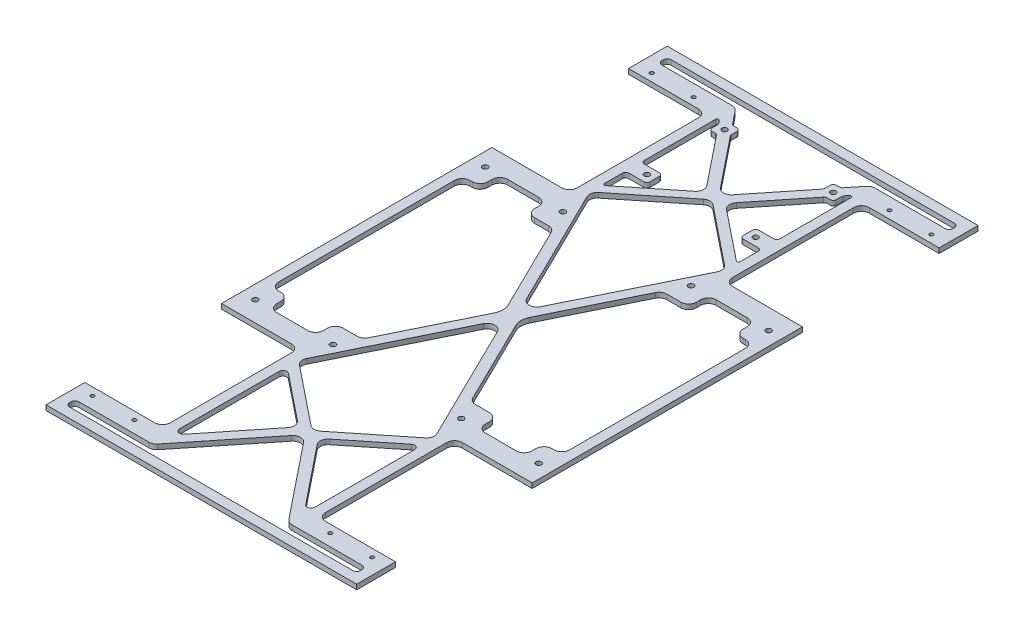
SolidWorks part; units mm, degrees
material "1060 Alloy"
ref_plane "Front Plane" through (0, 0, 0) normal (0, 0, 1) x (1, 0, 0)
ref_plane "Top Plane" through (0, 0, 0) normal (0, 1, 0) x (1, 0, 0)
ref_plane "Right Plane" through (0, 0, 0) normal (1, 0, 0) x (0, 0, -1)
sketch "Sketch1" plane through (0, 0, 0) normal (0, 1, 0) x (1, 0, 0)
  line L0 (-100, 87) -> (-100, -87)
  line L1 (-100, 200) -> (100, 200)
  line L2 (-100, 200) -> (-100, 175)
  line L3 (-100, -200) -> (100, -200)
  line L4 (100, 200) -> (100, 175)
  line L5 (-100, 175) -> (-50, 175)
  line L7 (-100, 87) -> (-50, 87)
  line L8 (-50, 175) -> (-50, 87)
  line L9 (-100, -87) -> (-50, -87)
  line L11 (-100, -175) -> (-50, -175)
  line L12 (-50, -87) -> (-50, -175)
  line L13 (100, -175) -> (50, -175)
  line L15 (100, -87) -> (50, -87)
  line L17 (100, 175) -> (50, 175)
  line L19 (100, 87) -> (50, 87)
  line L20 (50, 175) -> (50, 87)
  line L21 (-100, -175) -> (-100, -200)
  line L22 (100, 87) -> (100, -87)
  line L23 (100, -175) -> (100, -200)
  line L24 (50, -87) -> (50, -175)
  point P4 (0, 200)
  point P6 (100, 0)
  dimension "D1" = 400
  dimension "D2" = 200
  dimension "D3" = 88
  dimension "D4" = 25
  dimension "D5" = 50
extrude "Boss-Extrude1" add sketch "Sketch1" along normal blind 3.175
hole_wizard "3/32 (0.09375) Diameter Hole1" positions "Sketch3" profile "Sketch4" hole size "3/32" standard "ANSI Inch" end condition up to next
sketch "Sketch3" plane through (0, 3.175, 0) normal (0, 1, 0) x (1, 0, 0)
  line L0 (-90, 180) -> (-63.06, 180) construction
  line L5 (-100, 175) -> (-50, 175) construction
  line L6 (-100, 200) -> (-100, 175) construction
  point P0 (-90, 180)
  point P2 (-63.06, 180)
  dimension "D1" = 26.94
  dimension "D2" = 5
  dimension "D3" = 10
  dimension "D4" = 26.94
sketch "Sketch4" plane through (-90, 3.175, -180) normal (1, 0, 0) x (0, 0, 1)
  line L0 (0, 0) -> (0, 3.175)
  line L1 (0, 3.175) -> (1.1906, 3.175)
  line L2 (1.1906, 3.175) -> (1.1906, 0)
  line L5 (1.1906, 0) -> (0, 0)
  line L11 (0, -6.35) -> (0, 107.95) construction
  dimension "Thru Hole Dia." = 2.3812
  dimension "Thru Hole Depth" = 3.175
mirror "Mirror5" about plane through (0, 0, 0) normal (1, 0, 0) of "3/32 (0.09375) Diameter Hole1" second plane through (0, 0, 0) second plane normal (0, 0, 1)
sketch "Sketch5" plane through (0, 3.175, 0) normal (0, 1, 0) x (1, 0, 0)
  line L3 (-34.9422, 61.6) -> (-52.125, 61.6)
  line L4 (-93.65, 61.6) -> (-93.65, 0)
  line L5 (-93.65, 0) -> (-4.7456, 0)
  line L6 (-4.7456, 0) -> (-34.9422, 61.6)
  line L9 (-43.65, 177.5456) -> (-43.65, 101.1091)
  line L10 (-43.65, 101.1091) -> (-6.35, 131)
  line L11 (-6.35, 131) -> (-43.65, 177.5456)
  line L12 (-43.65, 93.79) -> (0, 128.7696)
  line L13 (0, 128.7696) -> (0, 4.7456)
  line L14 (0, 4.7456) -> (-43.65, 93.79)
  line L15 (-93.65, 193.65) -> (-93.65, 187.7)
  line L16 (-93.65, 187.7) -> (-43.65, 187.7)
  line L17 (-43.65, 187.7) -> (0, 133.2304)
  line L18 (0, 133.2304) -> (0, 193.65)
  line L19 (0, 193.65) -> (-93.65, 193.65)
  line L20 (-50, 175) -> (-50, 87) construction
  line L21 (0, 128.7696) -> (0, 133.2304) construction
  line L22 (100, 200) -> (-100, 200) construction
  line L23 (-100, 87) -> (-100, -87) construction
  line L24 (-100, 200) -> (-100, 175) construction
  line L25 (-100, 175) -> (-50, 175) construction
  line L26 (-50, 87) -> (-100, 87) construction
  line L27 (-4.7456, 0) -> (0, 0) construction
  line L28 (0, 0) -> (0, 4.7456) construction
  line L29 (-82.125, 61.6) -> (-93.65, 61.6)
  line L31 (-82.125, 61.6) -> (-82.125, 74.3)
  line L32 (-82.125, 74.3) -> (-52.125, 74.3)
  line L33 (-52.125, 61.6) -> (-52.125, 74.3)
  point P9 (0, 131)
  point P19 (-50, 131)
  dimension "D1" = 6.35
  dimension "D2" = 6.35
  dimension "D3" = 6.35
  dimension "D4" = 6.35
  dimension "D5" = 12.7
  dimension "D6" = 25.4
  dimension "D7" = 6.35
  dimension "D8" = 6.35
  dimension "D9" = 6.35
  dimension "D10" = 12.7
  dimension "D11" = 30
  dimension "D12" = 2.125
extrude "Cut-Extrude1" cut sketch "Sketch5" against normal through all both and the other way through all
mirror "Mirror6" about plane through (0, 0, 0) normal (1, 0, 0) of "Cut-Extrude1" second plane through (0, 0, 0) second plane normal (0, 0, 1)
hole_wizard "Ø3.5 (3.5) Diameter Hole1" positions "Sketch6" profile "Sketch7" hole size "Ø3.5" standard "ANSI Metric" end condition up to next
sketch "Sketch6" plane through (0, 0, 0) normal (0, -1, 0) x (-1, 0, 0)
  line L0 (41.24, 74) -> (91.24, 74) construction
  line L2 (50, 87) -> (100, 87) construction
  line L3 (91.24, 74) -> (100, 74) construction
  line L4 (100, 87) -> (100, -87) construction
  point P0 (41.24, 74)
  point P2 (91.24, 74)
  dimension "D1" = 50
  dimension "D2" = 8.76
  dimension "D3" = 13
sketch "Sketch7" plane through (-41.24, 0, -74) normal (1, 0, 0) x (0, 0, -1)
  line L0 (0, 0) -> (0, 3.175)
  line L1 (0, 3.175) -> (1.75, 3.175)
  line L2 (1.75, 3.175) -> (1.75, 0)
  line L5 (1.75, 0) -> (0, 0)
  line L11 (0, -6.35) -> (0, 107.95) construction
  dimension "Thru Hole Dia." = 3.5
  dimension "Thru Hole Depth" = 3.175
mirror "Mirror7" about plane through (0, 0, 0) normal (1, 0, 0) of "Ø3.5 (3.5) Diameter Hole1" second plane through (0, 0, 0) second plane normal (0, 0, 1)
sketch "Sketch8" plane through (0, 3.175, 0) normal (0, 1, 0) x (1, 0, 0)
  line L0 (-35, 171.8287) -> (35, 171.8287) construction
  line L1 (-40, 116.8287) -> (-30, 116.8287)
  line L3 (-40, 126.8287) -> (-30, 126.8287)
  line L4 (-30, 116.8287) -> (-30, 126.8287)
  line L13 (30, 116.8287) -> (40, 116.8287)
  line L14 (30, 116.8287) -> (30, 126.8287)
  line L15 (30, 126.8287) -> (40, 126.8287)
  line L17 (35, 171.8287) -> (35, 121.8287) construction
  line L18 (35, 121.8287) -> (-35, 121.8287) construction
  line L19 (-35, 121.8287) -> (-35, 171.8287) construction
  line L20 (-40, 166.8287) -> (-40, 176.8287)
  line L21 (-37.4776, 169.8432) -> (-32.5224, 173.8142) construction
  line L23 (-6.35, 131) -> (-43.65, 177.5456) construction
  line L24 (-43.65, 187.7) -> (0, 133.2304) construction
  line L29 (-43.65, 177.5456) -> (-43.65, 101.1091) construction
  line L36 (-40, 166.8287) -> (-30, 166.8287)
  line L38 (-40, 126.8287) -> (-43.65, 126.8287)
  line L41 (30, 166.8287) -> (40, 166.8287)
  line L44 (-40, 176.8287) -> (-30, 176.8287)
  line L45 (-30, 176.8287) -> (-30, 166.8287)
  line L46 (30, 166.8287) -> (30, 176.8287)
  line L47 (30, 176.8287) -> (40, 176.8287)
  line L48 (40, 176.8287) -> (40, 166.8287)
  line L49 (-40, 116.8287) -> (-43.65, 116.8287)
  line L50 (-43.65, 126.8287) -> (-43.65, 116.8287)
  line L51 (43.65, 177.5456) -> (43.65, 101.1091) construction
  line L52 (40, 126.8287) -> (43.65, 126.8287)
  line L54 (40, 116.8287) -> (43.65, 116.8287)
  line L55 (43.65, 126.8287) -> (43.65, 116.8287)
  point P22 (-35, 166.8287)
  point P23 (35, 166.8287)
  point P24 (-35, 126.8287)
  point P25 (30, 121.8287)
  point P26 (35, 126.8287)
  point P27 (-30, 121.8287)
  point P29 (0, 171.8287)
  point P34 (-35, 171.8287)
  dimension "D1" = 10
  dimension "D2" = 10
  dimension "D3" = 70
  dimension "D4" = 50
  dimension "D5" = 10
  dimension "D6" = 10
  dimension "D7" = 5
  dimension "D8" = 10
  dimension "D9" = 13.65
  dimension "D10" = 13.65
extrude "Boss-Extrude2" add sketch "Sketch8" against normal up to surface (3.175 mm away) up to face at (61.4562, 0, 0)
hole_wizard "M3 Clearance Hole1" positions "Sketch9" profile "Sketch10" hole size "M3" standard "ANSI Metric" end condition up to next
sketch "Sketch9" plane through (0, 3.175, 0) normal (0, 1, 0) x (1, 0, 0)
  line L0 (-35, 171.8287) -> (35, 171.8287) construction
  line L1 (35, 171.8287) -> (35, 121.8287) construction
  line L2 (35, 121.8287) -> (-35, 121.8287) construction
  line L3 (-35, 121.8287) -> (-35, 171.8287) construction
  line L6 (-30, 176.8287) -> (-34.9381, 176.8287) construction
  point P0 (-35, 171.8287)
  point P2 (35, 171.8287)
  point P4 (35, 121.8287)
  point P6 (-35, 121.8287)
  point P19 (0, 121.8287)
  dimension "D1" = 70
  dimension "D2" = 50
  dimension "D3" = 5
sketch "Sketch10" plane through (-35, 3.175, -171.8287) normal (1, 0, 0) x (0, 0, 1)
  line L0 (0, 0) -> (0, 3.175)
  line L1 (0, 3.175) -> (1.7, 3.175)
  line L2 (1.7, 3.175) -> (1.7, 0)
  line L5 (1.7, 0) -> (0, 0)
  line L11 (0, -6.35) -> (0, 107.95) construction
  dimension "Thru Hole Dia." = 3.4
  dimension "Thru Hole Depth" = 3.175
sketch "Sketch11" [suppressed] plane through (0, 3.175, 0) normal (0, 1, 0) x (1, 0, 0)
  line L1 (-43.65, 187.7) -> (43.65, 187.7)
  line L2 (-43.65, 187.7) -> (-43.65, 94.2145)
  line L3 (-43.65, 94.2145) -> (43.65, 94.2145)
  line L4 (43.65, 187.7) -> (43.65, 94.2145)
extrude "Cut-Extrude2" [suppressed] cut sketch "Sketch11" against normal up to surface (3.175 mm away)
fillet "Fillet1" radius 5 38 edges at (-34.9422, 1.5875, -61.6) (-93.65, 1.5875, -61.6) (-82.125, 1.5875, -61.6) (-82.125, 1.5875, -74.3) (-52.125, 1.5875, -74.3) (-52.125, 1.5875, -61.6) (-34.9422, 1.5875, 61.6) (-52.125, 1.5875, 61.6) (-52.125, 1.5875, 74.3) (-82.125, 1.5875, 74.3) (-82.125, 1.5875, 61.6) (-93.65, 1.5875, 61.6) (-6.35, 1.5875, 131) (-43.65, 1.5875, 93.79) (0, 1.5875, 128.7696) (-43.65, 1.5875, 187.7) (0, 1.5875, 133.2304) (34.9422, 1.5875, -61.6) (52.125, 1.5875, -61.6) (52.125, 1.5875, -74.3) (82.125, 1.5875, -74.3) (82.125, 1.5875, -61.6) (93.65, 1.5875, -61.6) (93.65, 1.5875, 61.6) (82.125, 1.5875, 61.6) (82.125, 1.5875, 74.3) (52.125, 1.5875, 74.3) (52.125, 1.5875, 61.6) (34.9422, 1.5875, 61.6) (6.35, 1.5875, 131) (43.65, 1.5875, 93.79) (43.65, 1.5875, 187.7)
fillet "Fillet2" radius 10 2 edges at (-4.7456, 1.5875, 0) (4.7456, 1.5875, 0)
fillet "Fillet3" radius 2.5 12 edges at (-93.65, 1.5875, -193.65) (-93.65, 1.5875, -187.7) (-43.65, 1.5875, 177.5456) (-43.65, 1.5875, 101.1091) (-93.65, 1.5875, 193.65) (-93.65, 1.5875, 187.7) (93.65, 1.5875, -193.65) (93.65, 1.5875, -187.7) (43.65, 1.5875, 177.5456) (43.65, 1.5875, 101.1091) (93.65, 1.5875, 187.7) (93.65, 1.5875, 193.65)
fillet "Fillet4" [suppressed] radius 5
fillet "Fillet5" radius 5 14 edges at (-43.65, 1.5875, -93.79) (-43.65, 1.5875, -187.7) (50, 1.5875, -175) (50, 1.5875, -87) (50, 1.5875, 87) (50, 1.5875, 175) (-50, 1.5875, 175) (-50, 1.5875, 87) (43.65, 1.5875, -93.79) (-50, 1.5875, -87) (-50, 1.5875, -175) (43.65, 1.5875, -187.7)
fillet "Fillet6" radius 5 4 edges at (-6.35, 1.5875, -131) (0, 1.5875, -128.7696) (0, 1.5875, -133.2304) (6.35, 1.5875, -131)
fillet "Fillet7" radius 2 20 edges at (-43.65, 1.5875, -116.8287) (-43.65, 1.5875, -126.8287) (-30, 1.5875, -126.8287) (-30, 1.5875, -116.8287) (-40, 1.5875, -172.9909) (-35.0619, 1.5875, -166.8287) (-34.9381, 1.5875, -176.8287) (-30, 1.5875, -170.6666) (-30, 1.5875, -176.8287) (-40, 1.5875, -166.8287) (35.0619, 1.5875, -166.8287) (40, 1.5875, -172.9909) (30, 1.5875, -170.6666) (34.9381, 1.5875, -176.8287) (30, 1.5875, -176.8287) (40, 1.5875, -166.8287) (30, 1.5875, -116.8287) (30, 1.5875, -126.8287) (43.65, 1.5875, -126.8287) (43.65, 1.5875, -116.8287)
fillet "Fillet8" radius 1 4 edges at (-43.65, 1.5875, -177.5456) (-43.65, 1.5875, -101.1091) (43.65, 1.5875, -177.5456) (43.65, 1.5875, -101.1091)
hole_wizard "trou raspberry" [suppressed] positions "Esquisse3D1" profile "Esquisse1" hole size "M2.5" standard "Ansi Metric"
sketch3d "Esquisse3D1"
  line L0 (92.5, 3.175, 14) -> (34.5, 3.175, 14) construction
  line L1 (34.5, 3.175, 14) -> (34.5, 3.175, -35) construction
  line L2 (34.5, 3.175, -35) -> (92.5, 3.175, -35) construction
  line L3 (92.5, 3.175, -35) -> (92.5, 3.175, 14) construction
  line L5 (100, 3.175, 87) -> (100, 3.175, -87) construction
  line L6 (50, 3.175, 87) -> (100, 3.175, 87) construction
  point P0 (92.5, 3.175, 14)
  point P2 (34.5, 3.175, 14)
  point P4 (34.5, 3.175, -35)
  point P6 (92.5, 3.175, -35)
  dimension "D1" = 58
  dimension "D2" = 49
  dimension "D3" = 7.5
  dimension "D4" = 73
sketch "Esquisse1" plane through (92.5, 3.175, 14) normal (1, 0, 0) x (0, 0, 1)
  line L0 (0, 0) -> (0, 3.175)
  line L1 (0, 3.175) -> (1.55, 3.175)
  line L2 (1.55, 3.175) -> (1.55, 0)
  line L5 (1.55, 0) -> (0, 0)
  line L11 (0, -6.35) -> (0, 107.95) construction
  dimension "Diamètre du perçage jusqu'au prochain" = 3.1
  dimension "Profondeur du perçage jusqu'au prochain" = 3.175
hole_wizard "trou bno" [suppressed] positions "Esquisse3D2" profile "Esquisse2" hole size "M3" standard "Ansi Metric"
sketch3d "Esquisse3D2"
  line L0 (-100, 3.175, -87) -> (-100, 3.175, 87) construction
  line L1 (-100, 3.175, 87) -> (-50, 3.175, 87) construction
  point P0 (-34.5, 3.175, 19.125)
  point P2 (-34.5, 3.175, -19.125)
  dimension "D1" = 38.25
  dimension "D2" = 65.5
  dimension "D3" = 67.875
sketch "Esquisse2" plane through (-34.5, 3.175, 19.125) normal (1, 0, 0) x (0, 0, 1)
  line L0 (0, 0) -> (0, 3.175)
  line L1 (0, 3.175) -> (1.8, 3.175)
  line L2 (1.8, 3.175) -> (1.8, 0)
  line L5 (1.8, 0) -> (0, 0)
  line L11 (0, -6.35) -> (0, 107.95) construction
  dimension "Diamètre du perçage jusqu'au prochain" = 3.6
  dimension "Profondeur du perçage jusqu'au prochain" = 3.175
hole_wizard "trou dc-dc plaque arriere" [suppressed] positions "Esquisse3D4" profile "Esquisse4" hole size "M3" standard "Ansi Metric"
sketch3d "Esquisse3D4"
  line L0 (-100, 3.175, 200) -> (100, 3.175, 200) construction
  line L1 (50, 3.175, 175) -> (50, 3.175, 87) construction
  line L2 (50, 3.175, 87) -> (100, 3.175, 87) construction
  line L3 (100, 3.175, 200) -> (100, 3.175, 175) construction
  point P0 (38.1, 3.175, 191.618)
  point P2 (-38.1, 3.175, 191.618)
  point P4 (-25.6, 3.175, 163.55)
  point P6 (25.4, 3.175, 163.55)
  point P8 (25.4, 3.175, 125.45)
  point P10 (-25.6, 3.175, 125.45)
  dimension "D1" = 76.2
  dimension "D2" = 8.382
  dimension "D3" = 51
  dimension "D4" = 38.1
  dimension "D5" = 24.6
  dimension "D6" = 38.45
  dimension "D7" = 61.9
sketch "Esquisse4" plane through (38.1, 3.175, 191.618) normal (1, 0, 0) x (0, 0, 1)
  line L0 (0, 0) -> (0, 3.175)
  line L1 (0, 3.175) -> (1.8, 3.175)
  line L2 (1.8, 3.175) -> (1.8, 0)
  line L5 (1.8, 0) -> (0, 0)
  line L11 (0, -6.35) -> (0, 107.95) construction
  dimension "Diamètre du perçage jusqu'au prochain" = 3.6
  dimension "Profondeur du perçage jusqu'au prochain" = 3.175
hole_wizard "trou arduino1" [suppressed] positions "Esquisse5" profile "Esquisse6" hole size "M3" standard "Ansi Metric"
sketch "Esquisse5" plane through (0, 3.175, 0) normal (0, 1, 0) x (1, 0, 0)
  point P0 (-24.13, 168.41)
  point P2 (24.13, 169.68)
  point P4 (-8.89, 117.61)
  point P6 (-24.13, 93.48)
  point P8 (24.13, 87.13)
  point P10 (19.05, 117.61)
sketch "Esquisse6" plane through (-24.13, 3.175, -168.41) normal (1, 0, 0) x (0, 0, 1)
  line L0 (0, 0) -> (0, 3.175)
  line L1 (0, 3.175) -> (1.8, 3.175)
  line L2 (1.8, 3.175) -> (1.8, 0)
  line L5 (1.8, 0) -> (0, 0)
  line L11 (0, -6.35) -> (0, 107.95) construction
  dimension "Diamètre du perçage jusqu'au prochain" = 3.6
  dimension "Profondeur du perçage jusqu'au prochain" = 3.175
hole_wizard "Dégagement M35" [suppressed] positions "Esquisse3D5" profile "Esquisse7" hole size "M3" standard "Ansi Metric"
sketch3d "Esquisse3D5"
  line L0 (100, 3.175, -200) -> (-100, 3.175, -200) construction
  line L1 (-50, 3.175, -175) -> (-50, 3.175, -87) construction
  point P0 (24.3241, 3.175, -178.427)
  point P2 (-23.9359, 3.175, -184.777)
  point P4 (-19.05, 3.175, -154.6317)
  point P6 (8.89, 3.175, -154.6317)
  point P8 (-23.9359, 3.175, -102.227)
  point P10 (24.3241, 3.175, -103.497)
  dimension "D1" = 82.55
  dimension "D2" = 27.94
  dimension "D3" = 74.93
  dimension "D4" = 15.223
  dimension "D5" = 26.0641
  dimension "D6" = 48.676
  dimension "D7" = 48.2767
  dimension "D8" = 52.6321
  dimension "D9" = 53.4133
sketch "Esquisse7" plane through (24.3241, 3.175, -178.427) normal (1, 0, 0) x (0, 0, 1)
  line L0 (0, 0) -> (0, 3.175)
  line L1 (0, 3.175) -> (1.8, 3.175)
  line L2 (1.8, 3.175) -> (1.8, 0)
  line L5 (1.8, 0) -> (0, 0)
  line L11 (0, -6.35) -> (0, 107.95) construction
  dimension "Diamètre du perçage jusqu'au prochain" = 3.6
  dimension "Profondeur du perçage jusqu'au prochain" = 3.175
hole_wizard "Dégagement M36" [suppressed] positions "Esquisse3D6" profile "Esquisse8" hole size "M3" standard "Ansi Metric"
sketch3d "Esquisse3D6"
  line L0 (45, 3.175, 42.5) -> (-45, 3.175, -42.5) construction
  line L2 (-45, 3.175, 42.5) -> (45, 3.175, -42.5) construction
  line L4 (0, 3.175, 0) -> (100, 3.175, 0) construction
  line L5 (100, 3.175, 87) -> (100, 3.175, -87) construction
  line L7 (0, 3.175, 0) -> (-100, 3.175, 0) construction
  line L8 (-100, 3.175, -87) -> (-100, 3.175, 87) construction
  point P0 (45, 3.175, 42.5)
  point P2 (-45, 3.175, 42.5)
  point P4 (-45, 3.175, -42.5)
  point P6 (45, 3.175, -42.5)
  point P24 (100, 3.175, 0)
  dimension "D1" = 90
  dimension "D2" = 85
sketch "Esquisse8" plane through (45, 3.175, 42.5) normal (1, 0, 0) x (0, 0, 1)
  line L0 (0, 0) -> (0, 3.175)
  line L1 (0, 3.175) -> (1.8, 3.175)
  line L2 (1.8, 3.175) -> (1.8, 0)
  line L5 (1.8, 0) -> (0, 0)
  line L11 (0, -6.35) -> (0, 107.95) construction
  dimension "Diamètre du perçage jusqu'au prochain" = 3.6
  dimension "Profondeur du perçage jusqu'au prochain" = 3.175
sketch "Esquisse11" [suppressed] plane through (0, 3.175, 0) normal (0, 1, 0) x (1, 0, 0)
  line L0 (-76, -37) -> (-76, -24) construction
  line L1 (-78, -37) -> (-78, -24)
  line L2 (-74, -37) -> (-74, -24)
  line L3 (-100, 87) -> (-100, -87) construction
  line L4 (-100, -87) -> (-50, -87) construction
  line L5 (-76, 21) -> (-76, 34) construction
  line L6 (-78, 21) -> (-78, 34)
  line L7 (-74, 21) -> (-74, 34)
  arc A0 (-78, -37) -> (-74, -37) centre (-76, -37) ccw
  arc A1 (-74, -24) -> (-78, -24) centre (-76, -24) ccw
  arc A2 (-78, 21) -> (-74, 21) centre (-76, 21) ccw
  arc A3 (-74, 34) -> (-78, 34) centre (-76, 34) ccw
  point P2 (-76, -30.5)
  point P7 (-76, 27.5)
  dimension "D3" = 13
  dimension "D1" = 4
  dimension "D2" = 24
  dimension "D4" = 50
  dimension "D5" = 4
  dimension "D6" = 45
  dimension "D7" = 13
extrude "Enlèv. mat.-Extru.1" [suppressed] cut sketch "Esquisse11" against normal up to surface (3.175 mm away)
sketch "Esquisse12" [suppressed] plane through (0, 3.175, 0) normal (0, 1, 0) x (1, 0, 0)
  line L0 (100, -87) -> (100, 87) construction
  line L5 (100, 200) -> (-100, 200) construction
  line L7 (12.5, 42.5) -> (-12.5, 42.5)
  line L8 (12.5, 42.5) -> (12.5, 57.5)
  line L9 (12.5, 57.5) -> (-12.5, 57.5)
  line L10 (-12.5, 42.5) -> (-12.5, 57.5)
  line L11 (12.5, 42.5) -> (-12.5, 57.5) construction
  line L12 (12.5, 57.5) -> (-12.5, 42.5) construction
  line L13 (-100, -200) -> (100, -200) construction
  line L14 (-100, 87) -> (-100, -87) construction
  point P5 (0, 50)
  dimension "D1" = 25
  dimension "D2" = 15
  dimension "D3" = 100
  dimension "D4" = 150
extrude "Enlèv. mat.-Extru.2" [suppressed] cut sketch "Esquisse12" against normal up to surface (3.175 mm away)
sketch "Esquisse13" [suppressed] plane through (0, 3.175, 0) normal (0, 1, 0) x (1, 0, 0)
  line L0 (-34.5, -15) -> (-34.5, 45) construction
  line L1 (-36.2, -15) -> (-36.2, 45)
  line L2 (-32.8, -15) -> (-32.8, 45)
  line L3 (-100, 87) -> (-100, -87) construction
  line L4 (100, 200) -> (-100, 200) construction
  arc A0 (-36.2, -15) -> (-32.8, -15) centre (-34.5, -15) ccw
  arc A1 (-32.8, 45) -> (-36.2, 45) centre (-34.5, 45) ccw
  point P2 (-34.5, 15)
  dimension "D1" = 1.7
  dimension "D2" = 65.5
  dimension "D3" = 60
  dimension "D4" = 185
extrude "Enlèv. mat.-Extru.3" [suppressed] cut sketch "Esquisse13" against normal up to surface (3.175 mm away)
sketch "Esquisse14" [suppressed] plane through (0, 3.175, 0) normal (0, 1, 0) x (1, 0, 0)
  line L0 (27, -108) -> (27, -18) construction
  line L1 (25.3, -108) -> (25.3, -18)
  line L2 (28.7, -108) -> (28.7, -18)
  line L3 (-27, -108) -> (-27, -18) construction
  line L4 (-28.7, -108) -> (-28.7, -18)
  line L5 (-25.3, -108) -> (-25.3, -18)
  line L6 (50, -175) -> (50, -87) construction
  line L7 (-100, -200) -> (100, -200) construction
  arc A0 (25.3, -108) -> (28.7, -108) centre (27, -108) ccw
  arc A1 (28.7, -18) -> (25.3, -18) centre (27, -18) ccw
  arc A2 (-28.7, -108) -> (-25.3, -108) centre (-27, -108) ccw
  arc A3 (-25.3, -18) -> (-28.7, -18) centre (-27, -18) ccw
  point P2 (27, -63)
  point P7 (-27, -63)
  dimension "D1" = 1.7
  dimension "D2" = 54
  dimension "D3" = 90
  dimension "D4" = 23
  dimension "D5" = 92
extrude "Enlèv. mat.-Extru.4" [suppressed] cut sketch "Esquisse14" against normal up to surface (3.175 mm away)
